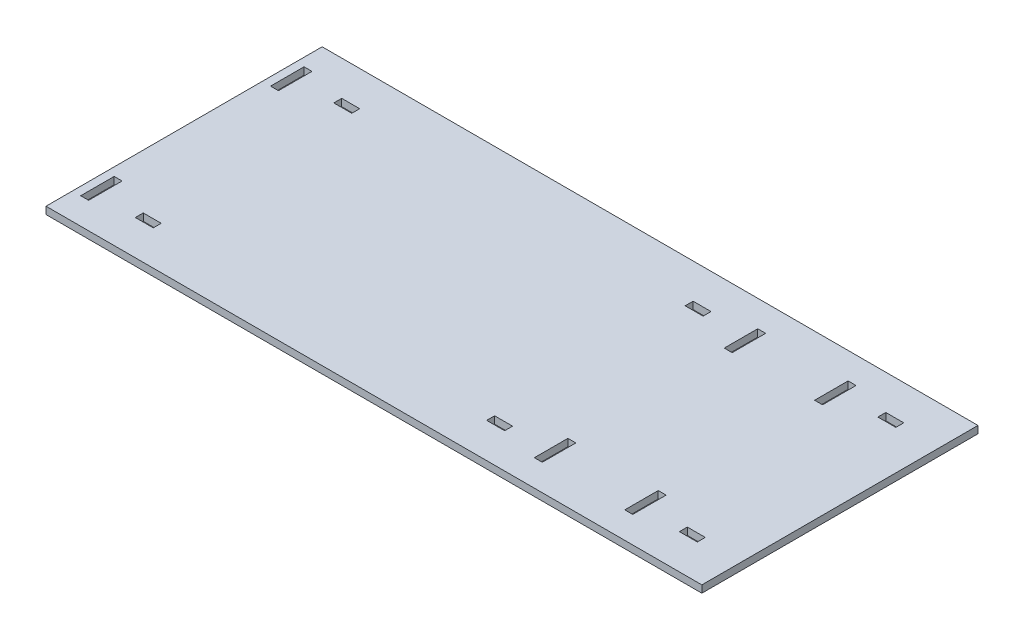
SolidWorks part; units mm, degrees
ref_plane "Front" through (0, 0, 0) normal (0, 0, 1) x (1, 0, 0)
ref_plane "Top" through (0, 0, 0) normal (0, 1, 0) x (1, 0, 0)
ref_plane "Right" through (0, 0, 0) normal (1, 0, 0) x (0, 0, -1)
sketch "Sketch1" plane through (0, 0, 0) normal (0, 1, 0) x (1, 0, 0)
  line L1 (-241.3, -101.6) -> (241.3, -101.6)
  line L2 (-241.3, -101.6) -> (-241.3, 101.6)
  line L3 (-241.3, 101.6) -> (241.3, 101.6)
  line L4 (241.3, -101.6) -> (241.3, 101.6)
  line L5 (-241.3, -101.6) -> (241.3, 101.6) construction
  line L6 (-241.3, 101.6) -> (241.3, -101.6) construction
  point P0 (0, 0)
  dimension "D1" = 482.6
  dimension "D2" = 203.2
extrude "Boss-Extrude1" add sketch "Sketch1" along normal blind 5.334 contours L2 L3 L4 L1
sketch "Sketch5" plane through (0, 0, 0) normal (0, -1, 0) x (1, 0, 0)
  line L0 (-241.3, 101.6) -> (241.3, 101.6) construction
  line L1 (-241.3, 101.6) -> (-241.3, -101.6) construction
  line L2 (212.002, -70.358) -> (199.429, -70.358) construction
  line L3 (199.429, -70.358) -> (199.429, -75.692) construction
  line L4 (199.429, -75.692) -> (212.002, -75.692) construction
  line L5 (212.002, -75.692) -> (212.002, -70.358) construction
  line L6 (170.727, -81.915) -> (170.727, -57.785) construction
  line L7 (170.727, -57.785) -> (165.393, -57.785) construction
  line L8 (165.393, -57.785) -> (165.393, -81.915) construction
  line L9 (165.393, -81.915) -> (170.727, -81.915) construction
  line L10 (170.727, 57.785) -> (170.727, 81.915) construction
  line L11 (170.727, 81.915) -> (165.393, 81.915) construction
  line L12 (165.393, 81.915) -> (165.393, 57.785) construction
  line L13 (165.393, 57.785) -> (170.727, 57.785) construction
  line L14 (212.002, 75.692) -> (199.429, 75.692) construction
  line L15 (199.429, 75.692) -> (199.429, 70.358) construction
  line L16 (199.429, 70.358) -> (212.002, 70.358) construction
  line L17 (212.002, 70.358) -> (212.002, 75.692) construction
  line L22 (98.9, 81.915) -> (98.9, 57.785) construction
  line L23 (98.9, 57.785) -> (104.234, 57.785) construction
  line L24 (104.234, 57.785) -> (104.234, 81.915) construction
  line L25 (104.234, 81.915) -> (98.9, 81.915) construction
  line L26 (98.9, -57.785) -> (98.9, -81.915) construction
  line L27 (98.9, -81.915) -> (104.234, -81.915) construction
  line L28 (104.234, -81.915) -> (104.234, -57.785) construction
  line L29 (104.234, -57.785) -> (98.9, -57.785) construction
  line L34 (-234.95, -57.785) -> (-234.95, -81.915) construction
  line L35 (-234.95, -81.915) -> (-229.616, -81.915) construction
  line L36 (-229.616, -81.915) -> (-229.616, -57.785) construction
  line L37 (-229.616, -57.785) -> (-234.95, -57.785) construction
  line L46 (-234.95, 81.915) -> (-234.95, 57.785) construction
  line L47 (-234.95, 57.785) -> (-229.616, 57.785) construction
  line L48 (-229.616, 57.785) -> (-229.616, 81.915) construction
  line L49 (-229.616, 81.915) -> (-234.95, 81.915) construction
  line L50 (-234.95, 81.915) -> (-229.616, 57.785) construction
  line L51 (-229.616, 81.915) -> (-234.95, 57.785) construction
  line L52 (98.9, 81.915) -> (104.234, 57.785) construction
  line L53 (-235.204, 57.531) -> (-229.362, 57.531)
  line L54 (-235.204, 57.531) -> (-235.204, 82.169)
  line L55 (-235.204, 82.169) -> (-229.362, 82.169)
  line L56 (-229.362, 57.531) -> (-229.362, 82.169)
  line L57 (-235.204, 57.531) -> (-229.362, 82.169) construction
  line L58 (-235.204, 82.169) -> (-229.362, 57.531) construction
  line L59 (165.393, 81.915) -> (170.727, 57.785) construction
  line L60 (165.393, -57.785) -> (170.727, -81.915) construction
  line L61 (98.9, -57.785) -> (104.234, -81.915) construction
  line L62 (-234.95, -57.785) -> (-229.616, -81.915) construction
  line L64 (98.646, 57.531) -> (104.488, 57.531)
  line L65 (98.646, 57.531) -> (98.646, 82.169)
  line L66 (98.646, 82.169) -> (104.488, 82.169)
  line L67 (104.488, 57.531) -> (104.488, 82.169)
  line L68 (98.646, 57.531) -> (104.488, 82.169) construction
  line L69 (98.646, 82.169) -> (104.488, 57.531) construction
  line L70 (165.139, 57.531) -> (170.981, 57.531)
  line L71 (165.139, 57.531) -> (165.139, 82.169)
  line L72 (165.139, 82.169) -> (170.981, 82.169)
  line L73 (170.981, 57.531) -> (170.981, 82.169)
  line L74 (165.139, 57.531) -> (170.981, 82.169) construction
  line L75 (165.139, 82.169) -> (170.981, 57.531) construction
  line L76 (165.139, -82.169) -> (170.981, -82.169)
  line L77 (165.139, -82.169) -> (165.139, -57.531)
  line L78 (165.139, -57.531) -> (170.981, -57.531)
  line L79 (170.981, -82.169) -> (170.981, -57.531)
  line L80 (165.139, -82.169) -> (170.981, -57.531) construction
  line L81 (165.139, -57.531) -> (170.981, -82.169) construction
  line L82 (98.646, -82.169) -> (104.488, -82.169)
  line L83 (98.646, -82.169) -> (98.646, -57.531)
  line L84 (98.646, -57.531) -> (104.488, -57.531)
  line L85 (104.488, -82.169) -> (104.488, -57.531)
  line L86 (98.646, -82.169) -> (104.488, -57.531) construction
  line L87 (98.646, -57.531) -> (104.488, -82.169) construction
  line L88 (-235.204, -82.169) -> (-229.362, -82.169)
  line L89 (-235.204, -82.169) -> (-235.204, -57.531)
  line L90 (-235.204, -57.531) -> (-229.362, -57.531)
  line L91 (-229.362, -82.169) -> (-229.362, -57.531)
  line L92 (-235.204, -82.169) -> (-229.362, -57.531) construction
  line L93 (-235.204, -57.531) -> (-229.362, -82.169) construction
  line L94 (70.5155, -70.104) -> (57.3075, -70.104)
  line L95 (199.429, 75.692) -> (212.002, 70.358) construction
  line L96 (199.429, -70.358) -> (212.002, -75.692) construction
  line L97 (70.5155, -70.104) -> (70.5155, -75.946)
  line L98 (-188.0235, -70.104) -> (-201.2315, -70.104)
  line L99 (70.5155, 75.946) -> (57.3075, 75.946)
  line L104 (-188.0235, -70.104) -> (-188.0235, -75.946)
  line L105 (-188.0235, -75.946) -> (-201.2315, -75.946)
  line L110 (-201.2315, -70.104) -> (-201.2315, -75.946)
  line L111 (-188.0235, -70.104) -> (-201.2315, -75.946) construction
  line L116 (70.5155, -75.946) -> (57.3075, -75.946)
  line L117 (57.3075, -70.104) -> (57.3075, -75.946)
  line L118 (199.1115, -75.946) -> (212.3195, -75.946)
  line L119 (199.1115, -75.946) -> (199.1115, -70.104)
  line L120 (199.1115, -70.104) -> (212.3195, -70.104)
  line L121 (212.3195, -75.946) -> (212.3195, -70.104)
  line L122 (199.1115, -75.946) -> (212.3195, -70.104) construction
  line L123 (199.1115, -70.104) -> (212.3195, -75.946) construction
  line L124 (199.1115, 70.104) -> (212.3195, 70.104)
  line L125 (199.1115, 70.104) -> (199.1115, 75.946)
  line L126 (199.1115, 75.946) -> (212.3195, 75.946)
  line L127 (212.3195, 70.104) -> (212.3195, 75.946)
  line L128 (199.1115, 70.104) -> (212.3195, 75.946) construction
  line L129 (199.1115, 75.946) -> (212.3195, 70.104) construction
  line L134 (70.5155, 75.946) -> (70.5155, 70.104)
  line L135 (70.5155, 70.104) -> (57.3075, 70.104)
  line L136 (57.3075, 75.946) -> (57.3075, 70.104)
  line L137 (70.5155, 75.946) -> (57.3075, 70.104) construction
  line L138 (70.5155, 70.104) -> (57.3075, 75.946) construction
  line L139 (70.5155, -70.104) -> (57.3075, -75.946) construction
  line L140 (70.5155, -75.946) -> (57.3075, -70.104) construction
  line L141 (-188.0235, -75.946) -> (-201.2315, -70.104) construction
  line L142 (-188.0235, 75.946) -> (-201.2315, 75.946)
  line L143 (-188.0235, 75.946) -> (-188.0235, 70.104)
  line L144 (-188.0235, 70.104) -> (-201.2315, 70.104)
  line L145 (-201.2315, 75.946) -> (-201.2315, 70.104)
  line L146 (-188.0235, 75.946) -> (-201.2315, 70.104) construction
  line L147 (-188.0235, 70.104) -> (-201.2315, 75.946) construction
  point P0 (-234.95, 81.915)
  point P21 (63.9115, 73.025)
  point P33 (63.9115, -73.025)
  point P41 (-194.6275, -73.025)
  point P46 (-194.6275, 73.025)
  point P53 (-232.283, 69.85)
  point P58 (101.567, 69.85)
  point P63 (168.06, 69.85)
  point P68 (168.06, -69.85)
  point P73 (101.567, -69.85)
  point P78 (-232.283, -69.85)
  point P98 (205.7155, -73.025)
  point P103 (205.7155, 73.025)
  dimension "D1" = 19.685
  dimension "D2" = 6.35
  dimension "D3" = 5.842
  dimension "D4" = 24.638
  dimension "D5" = 5.842
  dimension "D6" = 13.208
  dimension "D7" = 63.9115
  dimension "D8" = 46.6725
extrude "Cut-Extrude3" cut sketch "Sketch5" against normal through all
